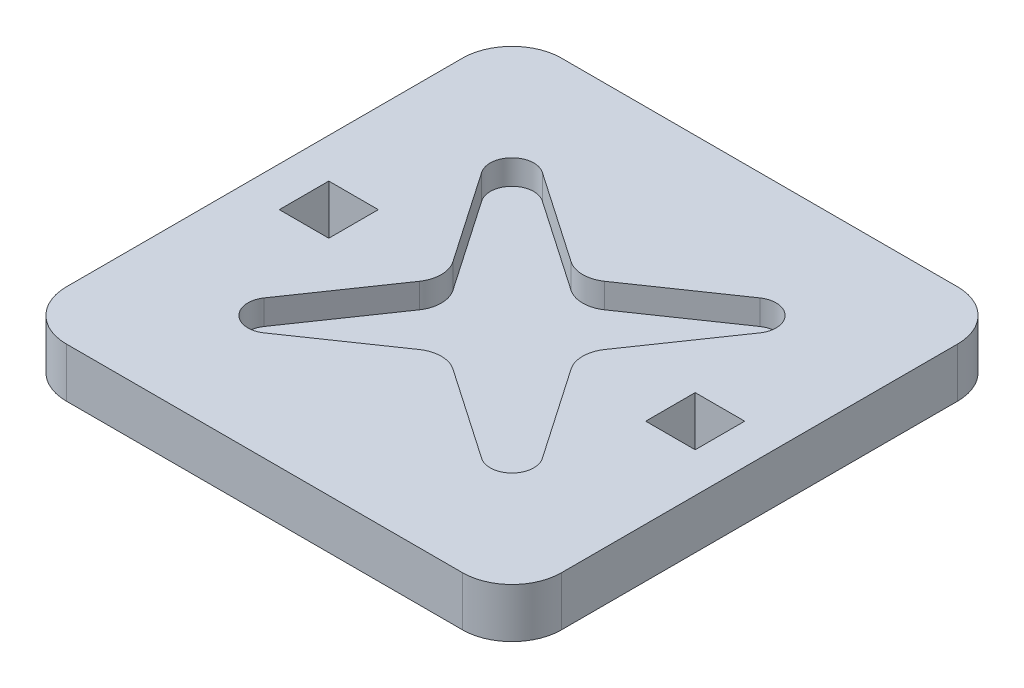
SolidWorks part; units mm, degrees
ref_plane "Front Plane" through (0, 0, 0) normal (0, 0, 1) x (1, 0, 0)
ref_plane "Top Plane" through (0, 0, 0) normal (0, 1, 0) x (1, 0, 0)
ref_plane "Right Plane" through (0, 0, 0) normal (1, 0, 0) x (0, 0, -1)
sketch "Sketch2" plane through (0, 0, 0) normal (0, 1, 0) x (1, 0, 0)
  line L0 (25, 0) -> (25, -50) construction
  line L1 (5, 0) -> (45, 0)
  line L2 (0, -5) -> (0, -45)
  line L3 (5, -50) -> (45, -50)
  line L4 (50, -5) -> (50, -45)
  line L5 (0, -25) -> (50, -25) construction
  line L7 (4, -27.5) -> (9, -27.5)
  line L8 (4, -27.5) -> (4, -22.5)
  line L9 (4, -22.5) -> (9, -22.5)
  line L10 (9, -27.5) -> (9, -22.5)
  line L11 (4, -27.5) -> (9, -22.5) construction
  line L12 (4, -22.5) -> (9, -27.5) construction
  line L13 (41, -27.5) -> (46, -27.5)
  line L14 (41, -27.5) -> (41, -22.5)
  line L15 (41, -22.5) -> (46, -22.5)
  line L16 (46, -27.5) -> (46, -22.5)
  line L17 (41, -27.5) -> (46, -22.5) construction
  line L18 (41, -22.5) -> (46, -27.5) construction
  arc A0 (0, -45) -> (5, -50) centre (5, -45) ccw
  arc A1 (45, -50) -> (50, -45) centre (45, -45) ccw
  arc A2 (50, -5) -> (45, 0) centre (45, -5) ccw
  arc A3 (0, -5) -> (5, 0) centre (5, -5) cw
  point P7 (0, -50)
  point P10 (50, -50)
  point P13 (50, 0)
  point P16 (0, 0)
  dimension "D3" = 5
  dimension "D5" = 5
  dimension "D1" = 50
  dimension "D2" = 50
  dimension "D7" = 5
  dimension "D8" = 5
  dimension "D9" = 5
extrude "Boss-Extrude1" add sketch "Sketch2" along normal blind 5
sketch "Sketch4" plane through (0, 5, 0) normal (0, 1, 0) x (1, 0, 0)
  line L0 (24.998, -24.9977) -> (24.998, -10.3985) construction
  line L1 (14.0106, -10.9513) -> (23.2996, -17.3312)
  line L2 (26.6965, -17.3312) -> (35.9854, -10.9513)
  line L3 (39.0444, -14.0103) -> (32.6645, -23.2993)
  line L4 (32.6645, -26.6962) -> (39.0444, -35.9851)
  line L5 (35.9854, -39.0441) -> (26.6965, -32.6642)
  line L6 (23.2996, -32.6642) -> (14.0106, -39.0441)
  line L7 (10.9516, -35.9851) -> (17.3315, -26.6962)
  line L8 (17.3315, -23.2993) -> (10.9516, -14.0103)
  line L9 (25, 0) -> (25, -50) construction
  line L10 (45, 0) -> (5, 0) construction
  line L11 (5, -50) -> (45, -50) construction
  line L12 (0, -25) -> (50, -25) construction
  line L13 (0, -5) -> (0, -45) construction
  line L14 (50, -45) -> (50, -5) construction
  arc A0 (14.0106, -10.9513) -> (11.2095, -11.2092) centre (12.7651, -12.7648) ccw
  arc A1 (39.0444, -14.0103) -> (35.9854, -10.9513) centre (37.2309, -12.7648) ccw
  arc A2 (23.2996, -17.3312) -> (26.6965, -17.3312) centre (24.998, -14.8583) ccw
  arc A7 (39.0444, -14.0103) -> (38.7866, -11.2092) centre (37.2309, -12.7648) ccw
  arc A12 (32.6645, -23.2993) -> (32.6645, -26.6962) centre (35.1374, -24.9977) ccw
  arc A13 (35.9854, -39.0441) -> (39.0444, -35.9851) centre (37.2309, -37.2306) ccw
  arc A14 (35.9854, -39.0441) -> (38.7866, -38.7863) centre (37.2309, -37.2306) ccw
  arc A19 (26.6965, -32.6642) -> (23.2996, -32.6642) centre (24.998, -35.1372) ccw
  arc A20 (10.9516, -35.9851) -> (14.0106, -39.0441) centre (12.7651, -37.2306) ccw
  arc A21 (10.9516, -35.9851) -> (11.2095, -38.7863) centre (12.7651, -37.2306) ccw
  arc A26 (17.3315, -26.6962) -> (17.3315, -23.2993) centre (14.8586, -24.9977) ccw
  arc A27 (14.0106, -10.9513) -> (10.9516, -14.0103) centre (12.7651, -12.7648) ccw
  point P0 (24.998, -24.9977)
  point P6 (24.998, -18.4977)
  point P13 (12.7651, -10.5648)
  point P70 (24.998, -24.9977)
  point P88 (25, -25)
  dimension "D3" = 4.4
  dimension "D4" = 4.4
  dimension "D6" = 3
  dimension "D1" = 19.5
  dimension "D2" = 19.5
  dimension "D5" = 6.5
extrude "Cut-Extrude1" cut sketch "Sketch4" against normal blind 2.5 contours A0 A27 L8 A26 L7 A20 L6 A19 L5 A13 L4 A12 L3 A1 L2 A2 L1
